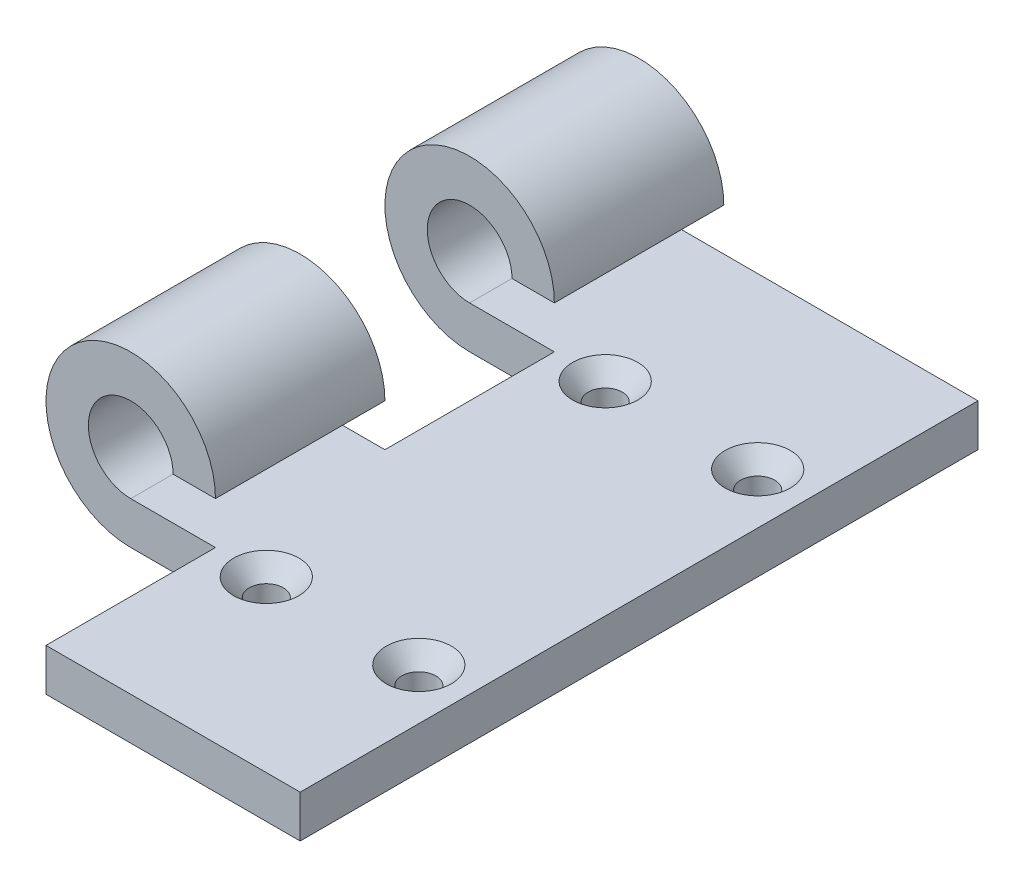
SolidWorks part; units mm, degrees
ref_plane "Front Plane" through (0, 0, 0) normal (0, 0, 1) x (1, 0, 0)
ref_plane "Top Plane" through (0, 0, 0) normal (0, 1, 0) x (1, 0, 0)
ref_plane "Right Plane" through (0, 0, 0) normal (1, 0, 0) x (0, 0, -1)
sketch "Sketch1" plane through (0, 0, 0) normal (0, 0, 1) x (1, 0, 0)
  line L0 (0, 0) -> (-50.8, 0)
  arc A0 (-50.8, 0) -> (-38.1, 12.7) centre (-50.8, 12.7) cw
  point P5 (0, 0)
  point P6 (0, 0)
  point P7 (0, 0)
  dimension "D2" = 12.7
  dimension "D1" = 50.8
extrude "Extrude-Thin2" add sketch "Sketch1" along normal mid plane 101.6 thin
sketch "Sketch2" plane through (0, 6.35, 0) normal (0, 1, 0) x (1, 0, 0)
  line L0 (-63.5, 50.8) -> (-63.5, -50.8) construction
  line L1 (-38.1, -50.8) -> (-63.5, -50.8)
  line L2 (-38.1, -50.8) -> (-38.1, -25.4)
  line L3 (-38.1, -25.4) -> (-63.5, -25.4)
  line L4 (-63.5, -50.8) -> (-63.5, -25.4)
  dimension "D1" = 25.4
extrude "Cut-Extrude1" cut sketch "Sketch2" against normal through all both and the other way through all
pattern_linear "LPattern1" count 2 spacing 50.8 along (0, 0, -1) of "Cut-Extrude1"
hole_wizard "CSK for #10 Flat Head Machine Screw1" positions "Sketch3" profile "Sketch4" countersink size "#10" standard "ANSI Inch" end condition through all
sketch "Sketch3" plane through (0, 6.35, 0) normal (0, 1, 0) x (1, 0, 0)
  point P0 (-30.48, 25.4)
  dimension "D1" = 7.62
  dimension "D2" = 25.4
sketch "Sketch4" plane through (-30.48, 6.35, -25.4) normal (1, 0, 0) x (0, 0, 1)
  line L0 (0, 0) -> (0, 6.35)
  line L1 (0, 6.35) -> (2.5527, 6.35)
  line L2 (2.5527, 6.35) -> (2.5527, 2.6882)
  line L3 (2.5527, 2.6882) -> (4.8895, 0)
  line L5 (4.8895, 0) -> (0, 0)
  line L6 (-2.5527, 2.6882) -> (-4.8895, 0) construction
  line L11 (0, -6.35) -> (0, 107.95) construction
  dimension "Thru Hole Dia." = 5.1054
  dimension "Thru Hole Depth" = 6.35
  dimension "Near C'Sink Dia." = 9.779
  dimension "Near C'Sink Angle" = 82
pattern_linear "LPattern2" count 2 spacing 50.8 along (0, 0, 1) count 2 spacing 22.86 along (1, 0, 0) of "CSK for #10 Flat Head Machine Screw1"
